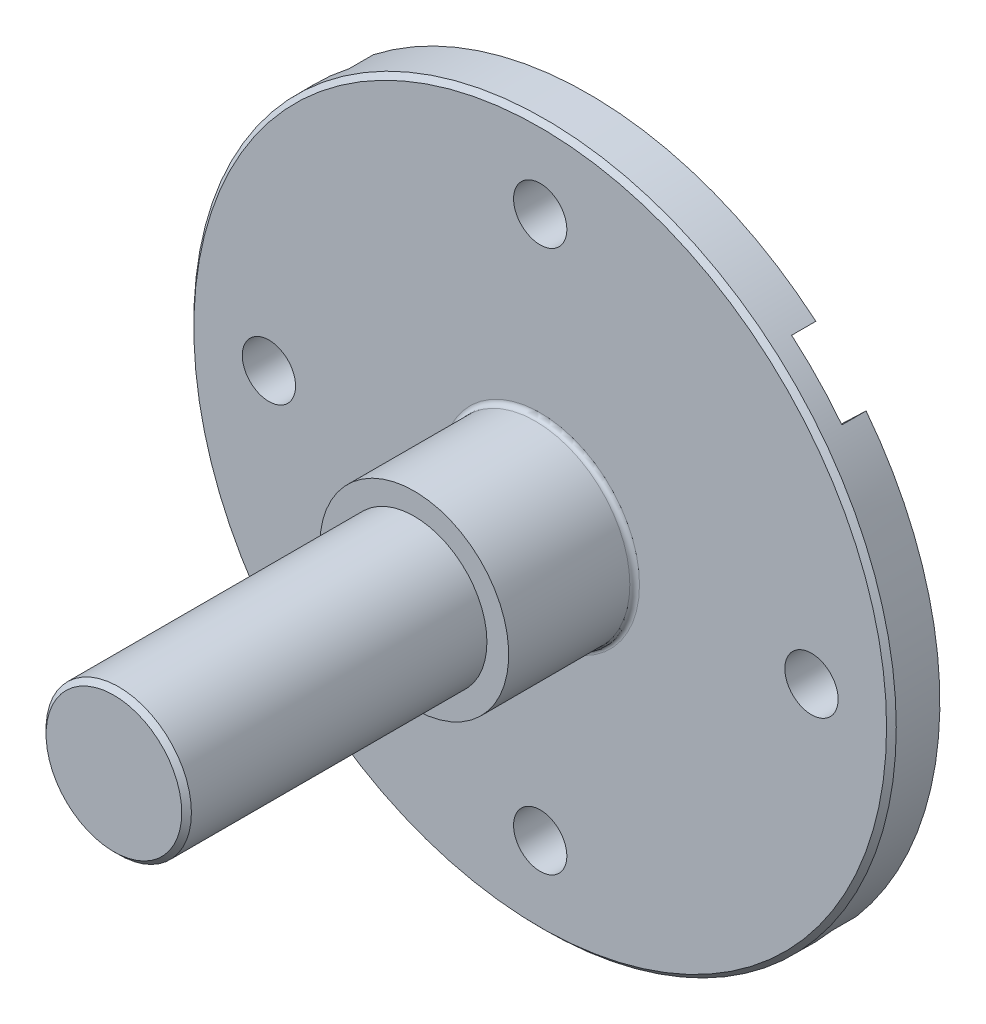
SolidWorks part; units mm, degrees
ref_plane "Piano frontale" through (0, 0, 0) normal (0, 0, 1) x (1, 0, 0)
ref_plane "Piano superiore" through (0, 0, 0) normal (0, 1, 0) x (1, 0, 0)
ref_plane "Piano destro" through (0, 0, 0) normal (1, 0, 0) x (0, 0, -1)
sketch "Schizzo1" plane through (0, 0, 0) normal (0, 0, 1) x (1, 0, 0)
  circle A0 centre (0, 0) radius 72.5
  dimension "D1" = 145
extrude "Estrusione1" add sketch "Schizzo1" along normal blind 10
sketch "Schizzo2" plane through (0, 0, 10) normal (0, 0, 1) x (1, 0, 0)
  circle A0 centre (0, 0) radius 19.5
  dimension "D1" = 39
extrude "Estrusione2" add sketch "Schizzo2" along normal blind 26
sketch "Schizzo5" plane through (0, 0, 36) normal (0, 0, 1) x (1, 0, 0)
  circle A0 centre (0, 0) radius 15
  dimension "D1" = 30
extrude "Estrusione5" add sketch "Schizzo5" along normal blind 62 and the other way blind 5
chamfer "Smusso2" distance 1 angle 45 1 edges at (72.5, 0, 10)
fillet "Raccordo1" radius 1 1 edges at (19.5, 0, 10)
sketch "Schizzo3" plane through (0, 0, 0) normal (0, 0, -1) x (-1, 0, 0)
  line L1 (-57.2713, 44.455) -> (-23.244, 11.8729)
  line L2 (-12.87, 22.7071) -> (-46.8973, 55.2892)
  circle A0 centre (0, 0) radius 72.5 construction
  arc A1 (-23.244, 11.8729) -> (-12.87, 22.7071) centre (-18.057, 17.29) ccw
  arc A5 (-46.8973, 55.2892) -> (-57.2713, 44.455) centre (0, 0) ccw
  dimension "D2" = 7.5
  dimension "D1" = 25
extrude "Estrusione3" cut sketch "Schizzo3" against normal blind 5
pattern_circular "RipetizioneCircolare1" count 4 over 360 about axis through (0, 0, 0) along (0, 0, 1) of "Estrusione3"
chamfer "Smusso3" distance 1 angle 45 1 edges at (15, 0, 98)
hole_wizard "M10 Giochi foro1" positions "Schizzo6" profile "Schizzo7" hole size "M10" standard "ISO" end condition through all
sketch "Schizzo6" plane through (8.7753, -26.1291, 10) normal (0, 0, 1) x (1, 0, 0)
  point P1 (-8.7762, 82.1292)
  point P3 (-8.7762, -29.8708)
  point P5 (-64.7762, 26.1292)
  point P7 (47.2238, 26.1292)
cosmetic thread "Filettatura del foro1" parameters "D1"=0, "D2"=21
cosmetic thread "Filettatura del foro2" parameters "D1"=0, "D2"=21
cosmetic thread "Filettatura del foro3" parameters "D1"=0, "D2"=21
cosmetic thread "Filettatura del foro4" parameters "D1"=0, "D2"=21
sketch "Schizzo7" plane through (-0.0013, 56, 10) normal (1, 0, 0) x (0, -1, 0)
  line L0 (0, 0) -> (0, 10)
  line L1 (0, 10) -> (5.5, 10)
  line L2 (5.5, 10) -> (5.5, 0)
  line L5 (5.5, 0) -> (0, 0)
  line L11 (0, -6.35) -> (0, 107.95) construction
  dimension "Thru Hole Dia." = 11
  dimension "Thru Hole Depth" = 10
